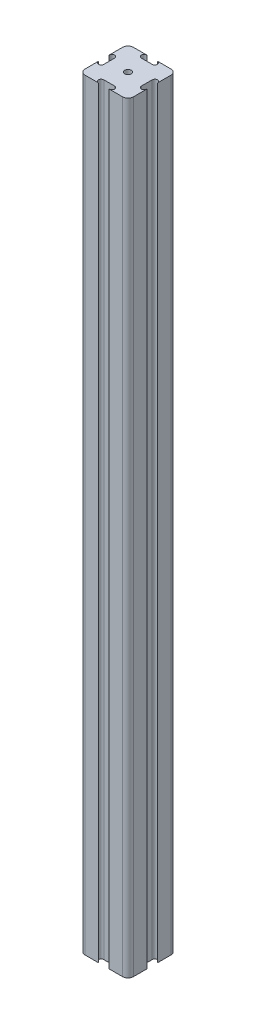
SolidWorks part; units mm, degrees
ref_plane "Front Plane" through (0, 0, 0) normal (0, 0, 1) x (1, 0, 0)
ref_plane "Top Plane" through (0, 0, 0) normal (0, 1, 0) x (1, 0, 0)
ref_plane "Right Plane" through (0, 0, 0) normal (1, 0, 0) x (0, 0, -1)
sketch "Esquisse4" plane through (0, 0, 0) normal (0, 1, 0) x (1, 0, 0)
  line L0 (-17.5, 22.5) -> (-5, 22.5)
  line L1 (22.5, 5) -> (22.5, 17.5)
  line L2 (0, 0) -> (22.5, 0) construction
  line L3 (5, 22.5) -> (17.5, 22.5)
  line L4 (0, 22.5) -> (0, 0) construction
  line L5 (-5, -17.5) -> (5, -17.5)
  line L6 (5, -22.5) -> (17.5, -22.5)
  line L7 (17.5, 5) -> (17.5, -5)
  line L8 (-5, -22.5) -> (-17.5, -22.5)
  line L10 (-5, 20) -> (5, 20) construction
  line L11 (0, 0) -> (0, -28.4326) construction
  line L12 (-5, 17.5) -> (5, 17.5)
  line L13 (17.5, 22.5) -> (17.5, -22.5) construction
  line L14 (-22.5, 17.5) -> (-22.5, 5)
  line L15 (-22.5, -5) -> (-22.5, -17.5)
  line L17 (-17.5, 5) -> (-17.5, -5)
  line L18 (0, 0) -> (-28.2169, 0) construction
  line L19 (22.5, -5) -> (22.5, -17.5)
  arc A0 (17.5, 22.5) -> (22.5, 17.5) centre (17.5, 17.5) cw
  arc A1 (17.5, -22.5) -> (22.5, -17.5) centre (17.5, -17.5) ccw
  arc A2 (-22.5, -17.5) -> (-17.5, -22.5) centre (-17.5, -17.5) ccw
  arc A3 (-17.5, 22.5) -> (-22.5, 17.5) centre (-17.5, 17.5) ccw
  arc A5 (-5, 22.5) -> (-5, 17.5) centre (-5, 20) ccw
  arc A6 (5, 17.5) -> (5, 22.5) centre (5, 20) ccw
  arc A7 (-5, -17.5) -> (-5, -22.5) centre (-5, -20) ccw
  arc A8 (5, -22.5) -> (5, -17.5) centre (5, -20) ccw
  arc A9 (-17.5, -5) -> (-22.5, -5) centre (-20, -5) cw
  arc A10 (22.5, -5) -> (17.5, -5) centre (20, -5) cw
  arc A11 (-17.5, 5) -> (-22.5, 5) centre (-20, 5) ccw
  arc A12 (22.5, 5) -> (17.5, 5) centre (20, 5) ccw
  point P8 (22.5, 22.5)
  point P13 (0, -17.5)
  point P20 (-22.5, 22.5)
  point P23 (0, 20)
  dimension "D4" = 5
  dimension "D6" = 5
  dimension "D7" = 5
  dimension "D8" = 5
  dimension "D20" = 10
  dimension "D24" = 12.5
  dimension "D2" = 22.5
  dimension "D3" = 45
  dimension "D5" = 10
  dimension "D10" = 10
  dimension "D11" = 12.5
  dimension "D12" = 22.5
  dimension "D13" = 5
  dimension "D14" = 17.5
  dimension "D15" = 12.5
  dimension "D16" = 45
  dimension "D17" = 2.5
  dimension "D18" = 5
  dimension "D19" = 45
  dimension "D21" = 5
  dimension "D22" = 17.5
  dimension "D23" = 10
  dimension "D25" = 5
extrude "Boss.-Extru.2" add sketch "Esquisse4" along normal blind 710 contours L15 A2 L8 A7 L5 A8 L6 A1 L19 A10 L7 A12 L1 A0 L3 A6 L12 A5 L0 A3 L14 A11 L17 A9
sketch "Esquisse5" plane through (0, 0, 0) normal (0, -1, 0) x (1, 0, 0)
  circle A0 centre (0, 0) radius 3
extrude "Enlèv. mat.-Extru.1" cut sketch "Esquisse5" against normal through all
